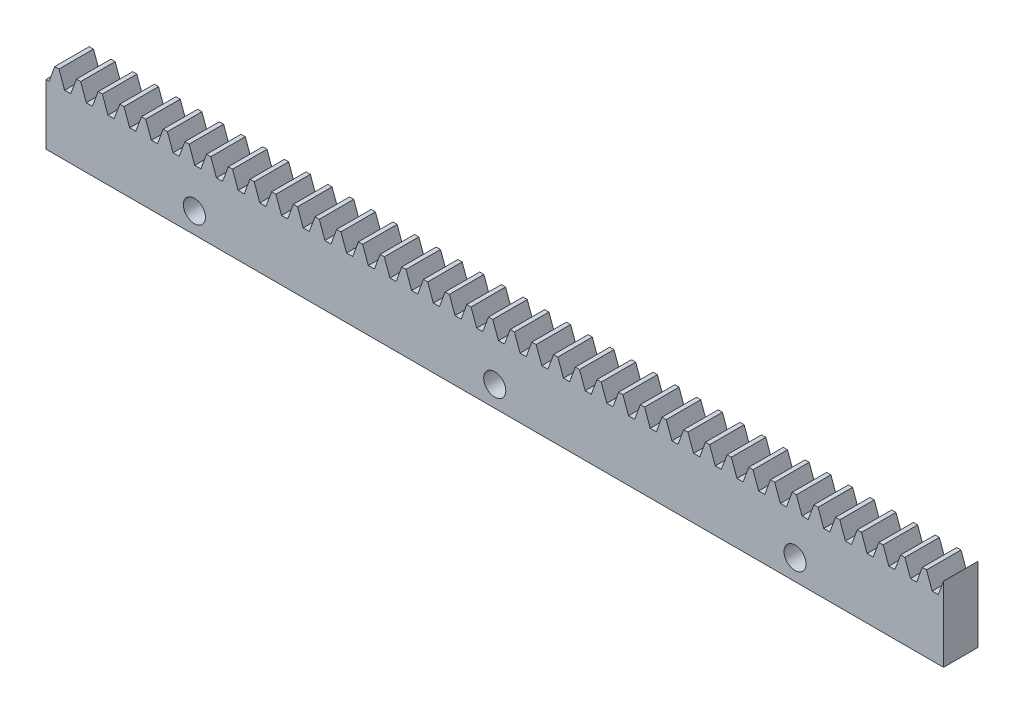
SolidWorks part; units mm, degrees
extrude "Blank" add sketch "BlankSke" against normal blind 5
sketch "BlankSke" plane through (0, 0, 0) normal (0, 0, 1) x (1, 0, 0)
  line L1 (0, 0) -> (130, 0)
  line L2 (0, 0) -> (0, 11)
  line L3 (0, 11) -> (130, 11)
  line L4 (130, 0) -> (130, 11)
  dimension "Length" = 130
  dimension "Blank_height" = 11
ref_plane "Plane1" through (0, 0, 0) normal (0, 0, 1) x (1, 0, 0)
ref_plane "Plane2" through (0, 0, 0) normal (0, 1, 0) x (1, 0, 0)
ref_plane "Plane3" through (0, 0, 0) normal (1, 0, 0) x (0, 0, -1)
sketch "HoldingSke" plane through (0, 0, 0) normal (0, 1, 0) x (1, 0, 0)
  line L0 (0, 0) -> (0.1392, 0.9903)
  line L1 (-15, 0) -> (100, 0) construction
  line L2 (0, 0) -> (-2.1039, 2.3779)
  line L3 (0, 0) -> (-11.863, 4.5341)
  line L4 (0, 0) -> (6.316, 5.8897)
  line L5 (0, 0) -> (-23.7986, -8.8762)
  line L6 (0, 0) -> (-10.5278, -7.1032)
  line L9 (-71.009, 38.7566) -> (51.1511, 83.2192)
  line L10 (-76.2, 3.3779) -> (-66.2, 3.3779)
  line L11 (0, 0) -> (-5, 0)
  line L12 (-76.2, 101.6) -> (-76.162, 101.6)
  line L13 (24.9733, 27.94) -> (52.9518, 28.4284)
  line L14 (24.9733, 27.94) -> (24.9743, 27.94)
  line L15 (24.9733, 27.94) -> (100.4006, 29.5858)
  circle A0 centre (0, 0) radius 19.05
  circle A1 centre (0, 0) radius 5
  circle A2 centre (0, 0) radius 12.7
  dimension "MPH" = 10
  dimension "Diameter" = 38.1
  dimension "Num_teeth" = 43
  dimension "Pitch" = 1
  dimension "Show_teeth" = 998
  dimension "Thickness" = 12.7
  dimension "Ap" = 20
  dimension "Pitch_height" = 10
  dimension "Width" = 5
  dimension "Backlash" = 0.038
  dimension "Addendum_fac" = 1
  dimension "Dedendum_fac" = 1.25
  dimension "Clearance_fac" = 0.25
  dimension "Dedendum_add" = 0.001
  dimension "Length" = 130
  dimension "Module" = 1
sketch "TooCutSkeIll" plane through (0, 0, 0) normal (0, 0, 1) x (1, 0, 0)
  line L0 (-1.2538, 10.9737) -> (-0.5045, 8.9152)
  line L1 (-0.2687, 8.75) -> (0.2687, 8.75)
  line L2 (0.5045, 8.9152) -> (1.2538, 10.9737)
  line L3 (130, 11) -> (0, 11) construction
  line L4 (0, 0) -> (0, 64.897) construction
  line L5 (-13.208, 10) -> (12.954, 10) construction
  line L6 (0, 0) -> (130, 0) construction
  line L7 (0.8994, 10) -> (0.8994, 48.7463) construction
  line L8 (-0.8994, 10) -> (-0.8994, 48.7463) construction
  line L9 (1.2914, 11) -> (1.2914, 11.0254)
  line L10 (-1.2914, 11) -> (-1.2914, 11.0254)
  line L11 (-1.2914, 11.0254) -> (1.2914, 11.0254)
  arc A0 (0.2687, 8.75) -> (0.5045, 8.9152) centre (0.2687, 9.001) ccw
  arc A1 (-0.5045, 8.9152) -> (-0.2687, 8.75) centre (-0.2687, 9.001) ccw
  arc A2 (1.2914, 11) -> (1.2538, 10.9737) centre (1.2914, 10.96) ccw
  arc A3 (-1.2538, 10.9737) -> (-1.2914, 11) centre (-1.2914, 10.96) ccw
  dimension "Pitch_height" = 10
  dimension "Addendum_plus" = 1.0254
  dimension "Pressure_angle" = 20
  dimension "Gap_width" = 1.7988
  dimension "Dedendum" = 1.25
extrude "ToothCutIll" [suppressed] cut sketch "TooCutSkeIll" against normal through all
sketch "TooCutSkeSim" plane through (0, 0, 0) normal (0, 0, 1) x (1, 0, 0)
  line L0 (0.4444, 8.75) -> (-0.4444, 8.75)
  line L1 (1.2726, 11.0254) -> (0.4444, 8.75)
  line L2 (0, 17.4625) -> (0, 53.467) construction
  line L3 (1.2726, 11.0254) -> (-1.2726, 11.0254)
  line L6 (-1.2726, 11.0254) -> (-0.4444, 8.75)
  line L9 (-0.8994, 10) -> (0.8994, 10) construction
  line L10 (0, 0) -> (130, 0) construction
  line L11 (0.8994, 10) -> (0.8994, 53.467) construction
  line L12 (-0.8994, 10) -> (-0.8994, 53.467) construction
  dimension "Pitch_height" = 10
  dimension "Addendum_plus" = 1.0254
  dimension "Pressure_angle" = 20
  dimension "Gap_width" = 1.7988
  dimension "Dedendum" = 1.25
extrude "ToothCutSim" cut sketch "TooCutSkeSim" against normal through all
pattern_linear "TeethCuts" count 42 spacing 3.1416 along (1, 0, 0) of "ToothCutIll", "ToothCutSim"
sketch "Esquisse1" plane through (0, 0, 0) normal (0, 0, 1) x (1, 0, 0)
  line L0 (0, 3) -> (130, 3) construction
  line L1 (0, 8.75) -> (0, 0) construction
  line L2 (130, 0) -> (130, 10.8113) construction
  line L3 (0, 0) -> (130, 0) construction
  circle A0 centre (21.5, 3) radius 1.6
  circle A1 centre (65, 3) radius 1.6
  circle A2 centre (108.5, 3) radius 1.6
  dimension "D2" = 3.2
  dimension "D3" = 3.2
  dimension "D4" = 3.2
  dimension "D5" = 21.5
  dimension "D6" = 21.5
  dimension "D1" = 3
extrude "Enlèv. mat.-Extru.1" cut sketch "Esquisse1" against normal blind 10
equation "' \"Module@HoldingSke\" = 6.35"
equation "' \"Num_teeth@HoldingSke\" = 12"
equation "' \"Ap@HoldingSke\" =  20"
equation "' \"Ap@HoldingSke\" = 20"
equation "' \"Width@HoldingSke\" = 0.25 * 25.4"
equation "' \"Show_teeth@HoldingSke\" = 500"
equation "' \"Backlash@HoldingSke\" = 0.009 * 25.4"
equation "' \"Addendum_fac@HoldingSke\" = 1.0"
equation "' \"Dedendum_fac@HoldingSke\" = 1.25"
equation "' \"Dedendum_add@HoldingSke\" = 0.00005 * 25.4"
equation "' \"Clearance_fac@HoldingSke\" = 0.25"
equation "' \"Pitch_height@HoldingSke\" = 1 * 25.4"
equation "' \"Length@HoldingSke\" = 4.71 * 25.4"
equation "\"Pitch@HoldingSke\" = 1 / \"Module@HoldingSke\""
equation "\"MPH@HoldingSke\" = \"Dedendum_fac@HoldingSke\" / \"Pitch@HoldingSke\" + 2 * \"Dedendum_add@HoldingSke\" + 0.002 * 25.4"
equation "\"MPH@HoldingSke\" = ((sgn( \"MPH@HoldingSke\" - \"Pitch_height@HoldingSke\")+1)*( \"MPH@HoldingSke\" - \"Pitch_height@HoldingSke\"))/2 + \"Pitch_height@HoldingSke\""
equation "\"Blank_height@BlankSke\" = \"Pitch_height@HoldingSke\" + \"Addendum_fac@HoldingSke\"  / \"Pitch@HoldingSke\" "
equation "\"Length@BlankSke\" =  \"Length@HoldingSke\""
equation "\"Face_width@Blank\" = \"Width@HoldingSke\""
equation "\"Pressure_angle@TooCutSkeIll\" = \"Ap@HoldingSke\""
equation "\"Addendum_plus@TooCutSkeIll\" =  \"Addendum_fac@HoldingSke\"  / \"Pitch@HoldingSke\" + 0.001 *25.4"
equation "\"Dedendum@TooCutSkeIll\" = \"Dedendum_fac@HoldingSke\"  / \"Pitch@HoldingSke\""
equation "\"Pitch_height@TooCutSkeIll\" =  \"MPH@HoldingSke\""
equation "\"Gap_width@TooCutSkeIll\" = 3.14159265 / 2 / \"Pitch@HoldingSke\" + 6 * \"Backlash@HoldingSke\""
equation "\"Pressure_angle@TooCutSkeSim\" = \"Ap@HoldingSke\""
equation "\"Addendum_plus@TooCutSkeSim\" =  \"Addendum_fac@HoldingSke\"  / \"Pitch@HoldingSke\" + 0.001 * 25.4"
equation "\"Dedendum@TooCutSkeSim\" = \"Dedendum_fac@HoldingSke\"  / \"Pitch@HoldingSke\""
equation "\"Pitch_height@TooCutSkeSim\" =  \"MPH@HoldingSke\""
equation "\"Gap_width@TooCutSkeSim\" = 3.14159265 / 2 / \"Pitch@HoldingSke\" + 6 * \"Backlash@HoldingSke\""
equation "\"Root_fillet@TooCutSkeIll\" = \"Clearance_fac@HoldingSke\" / \"Pitch@HoldingSke\" + \"Dedendum_add@HoldingSke\""
equation "\"Break_rad@TooCutSkeIll\" = 0.02 / \"Pitch@HoldingSke\" * 2"
equation "\"Linear_pitch@TeethCuts\" = 3.14159265 / \"Pitch@HoldingSke\""
equation "\"Num_teeth@HoldingSke\" = int( ( \"Length@HoldingSke\" + 0 ) / (3.14159265 / \"Pitch@HoldingSke\")) + 0.9999  + 1"
equation " \"Num_teeth@TeethCuts\" = int( \"Show_teeth@HoldingSke\" ) + 1"
equation " \"Num_teeth@TeethCuts\" = ((sgn( \"Num_teeth@TeethCuts\" - \"Num_teeth@HoldingSke\" )-1)*( \"Num_teeth@TeethCuts\" - \"Num_teeth@HoldingSke\" ))/-2+ \"Num_teeth@HoldingSke\""
equation " \"Num_teeth@TeethCuts\" = ((sgn( \"Num_teeth@TeethCuts\" - 2.0)+1)*( \"Num_teeth@TeethCuts\" - 2.0))/2 +2.0"
